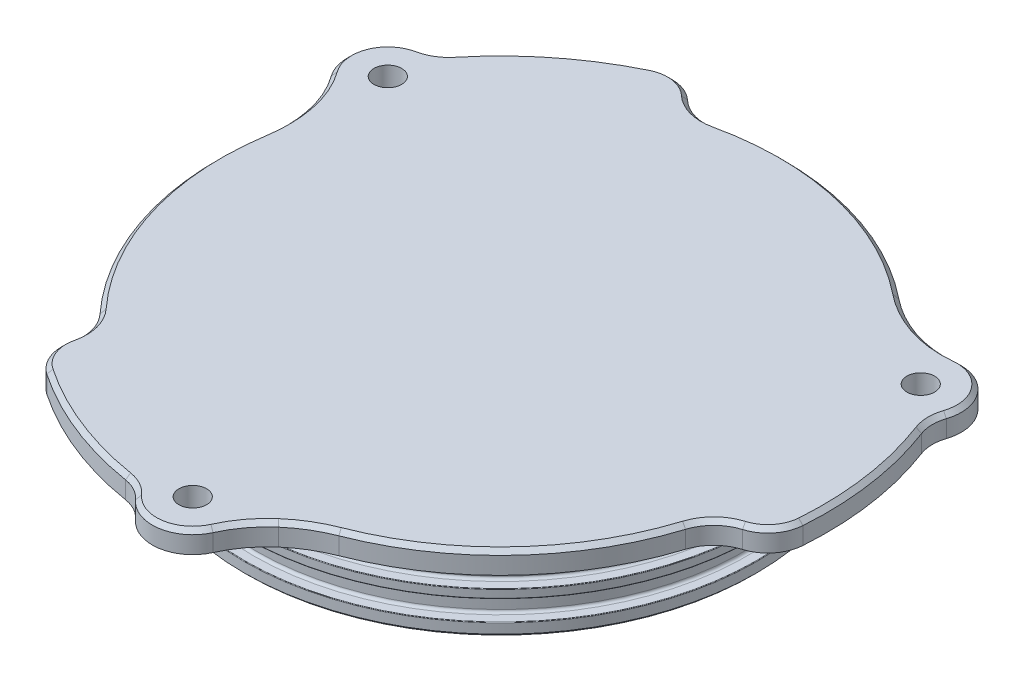
SolidWorks part; units mm, degrees
material "6061-T6 (SS)"
ref_plane "Front Plane" through (0, 0, 0) normal (0, 0, 1) x (1, 0, 0)
ref_plane "Top Plane" through (0, 0, 0) normal (0, 1, 0) x (1, 0, 0)
ref_plane "Right Plane" through (0, 0, 0) normal (1, 0, 0) x (0, 0, -1)
sketch "Sketch2" plane through (0, 0, 0) normal (0, 0, 1) x (1, 0, 0)
  line L0 (0, 0) -> (0, 50000) construction
  line L1 (0, 0) -> (-66.675, 0)
  line L2 (-66.675, 0) -> (-66.675, -5.08)
  line L3 (-66.675, -5.08) -> (-60.9219, -5.08)
  line L4 (-60.2869, -5.715) -> (-60.2869, -7.493)
  line L5 (-60.2869, -22.225) -> (-52.07, -22.225)
  line L6 (-52.07, -22.225) -> (-52.07, -5.08)
  line L7 (-52.07, -5.08) -> (0, -5.08)
  line L8 (0, 0) -> (0, -5.08)
  line L9 (-60.1599, -19.1516) -> (-58.1406, -19.1516)
  line L10 (-57.5056, -18.5166) -> (-57.5056, -15.0368)
  line L11 (-58.1406, -14.4018) -> (-60.1599, -14.4018)
  line L13 (-60.1599, -12.3698) -> (-58.1406, -12.3698)
  line L14 (-57.5056, -11.7348) -> (-57.5056, -8.255)
  line L15 (-58.1406, -7.62) -> (-60.1599, -7.62)
  line L16 (-60.2869, -12.4968) -> (-60.2869, -14.2748)
  line L17 (-60.2869, -19.2786) -> (-60.2869, -22.225)
  arc A0 (-60.1599, -19.1516) -> (-60.2869, -19.2786) centre (-60.1599, -19.2786) ccw
  arc A1 (-60.1599, -14.4018) -> (-60.2869, -14.2748) centre (-60.1599, -14.2748) cw
  arc A2 (-60.2869, -12.4968) -> (-60.1599, -12.3698) centre (-60.1599, -12.4968) cw
  arc A3 (-60.1599, -7.62) -> (-60.2869, -7.493) centre (-60.1599, -7.493) cw
  arc A5 (-60.9219, -5.08) -> (-60.2869, -5.715) centre (-60.9219, -5.715) cw
  arc A6 (-58.1406, -19.1516) -> (-57.5056, -18.5166) centre (-58.1406, -18.5166) ccw
  arc A7 (-57.5056, -15.0368) -> (-58.1406, -14.4018) centre (-58.1406, -15.0368) ccw
  arc A8 (-58.1406, -12.3698) -> (-57.5056, -11.7348) centre (-58.1406, -11.7348) ccw
  arc A9 (-57.5056, -8.255) -> (-58.1406, -7.62) centre (-58.1406, -8.255) ccw
  point P21 (-60.2869, -19.1516)
  point P26 (-60.2869, -12.3698)
  dimension "D9" = 0.127
  dimension "D10" = 0.635
  dimension "D1" = 133.35
  dimension "D2" = 120.5738
  dimension "D3" = 104.14
  dimension "D4" = 5.08
  dimension "D5" = 22.225
  dimension "D6" = 115.0112
  dimension "D7" = 2.54
  dimension "D8" = 4.7498
revolve "Revolve1" add sketch "Sketch2" angle 360 about L0
sketch "Sketch11" plane through (0, 0, 0) normal (0, 1, 0) x (1, 0, 0)
  line L0 (0, -9.8926) -> (0, 42839.8063) construction
  line L1 (-62.6916, 36.195) -> (43238.5786, -24963.805) construction
  arc A0 (-33.5526, 69.1219) -> (-59.5029, 48.6109) centre (0, 0) ccw
  circle A1 centre (0, 0) radius 66.675 construction
  arc A2 (-23.5859, 67.6058) -> (-14.4328, 65.0942) centre (-16.6321, 75.0133) ccw
  arc A3 (-64.6033, 45.5262) -> (-59.5029, 48.6109) centre (-66.3876, 54.2353) ccw
  arc A4 (-23.5859, 67.6058) -> (-33.5526, 69.1219) centre (-29.6705, 61.1243) ccw
  arc A7 (-65.8943, 10.1735) -> (-66.0808, 20.5541) centre (-96.0174, 14.8242) ccw
  arc A8 (-66.0808, 20.5541) -> (-70.4197, 30.6271) centre (-91.028, 15.7792) ccw
  arc A9 (-64.6033, 45.5262) -> (-70.4197, 30.6271) centre (-62.6916, 36.195) ccw
  arc A12 (-14.4328, 65.0942) -> (-65.8943, 10.1735) centre (0, 0) ccw
  dimension "D1" = 60
  dimension "D2" = 30.48
  dimension "D3" = 25.4
  dimension "D4" = 9.525
  dimension "D7" = 10.16
  dimension "D8" = 8.89
  dimension "D5" = 72.39
  dimension "D6" = 15.24
  dimension "D9" = 38.1
extrude "Boss-Extrude1" add sketch "Sketch11" against normal up to surface (5.08 mm away) up to face at (0, -5.08, -60.9219)
hole_wizard "1/4 Clearance Hole1" positions "Sketch13" profile "Sketch12" hole size "1/4" standard "Ansi Inch" end condition through all
sketch "Sketch13" plane through (-10.4599, 0, 18.1437) normal (0, 1, 0) x (-1, 0, 0)
  arc A1 (54.1434, -63.6698) -> (59.9598, -48.7707) centre (52.2317, -54.3387) ccw construction
  point P7 (52.2317, -54.3387)
sketch "Sketch12" plane through (-62.6916, 0, -36.195) normal (1, 0, 0) x (0, 0, 1)
  line L0 (0, 0) -> (0, 22.225)
  line L1 (0, 22.225) -> (3.2639, 22.225)
  line L2 (3.2639, 22.225) -> (3.2639, 0)
  line L5 (3.2639, 0) -> (0, 0)
  line L11 (0, -6.35) -> (0, 107.95) construction
  dimension "Thru Hole Dia." = 6.5278
  dimension "Thru Hole Depth" = 22.225
pattern_circular "CirPattern1" count 3 over 360 about axis through (0, 0, 0) along (0, 1, 0) of "Boss-Extrude1", "1/4 Clearance Hole1"
chamfer "Chamfer1" distance 0.635 angle 45 1 edges at (0, -22.225, -60.2869)
chamfer "Chamfer2" distance 1.016 angle 45 24 edges at (-9.4879, 0, 76.8232) (-28.3812, 0, 71.4012) (1.4367, 0, 81.806) (-46.3799, 0, 59.4942) (11.4827, 0, 71.5438) (-46.8179, 0, 49.3399) (19.4588, 0, 64.4472) (-63.8082, 0, 19.3407) (48.6537, 0, 45.5892) (-65.5423, 0, -15.3718) (66.1386, 0, 15.8756) (-67.7001, 0, -25.8276) (74.7134, 0, 10.419) (-71.5644, 0, -39.6588) (76.0258, 0, -11.1217) (-61.7869, 0, -46.6283) (71.2748, 0, -30.1948) (-47.6446, 0, -60.2794) (70.1278, 0, -42.1472) (-28.3336, 0, -69.9132) (56.2174, 0, -45.7162) (-19.3207, 0, -65.2155) (46.0835, 0, -49.0754) (15.1546, 0, -64.9299)
